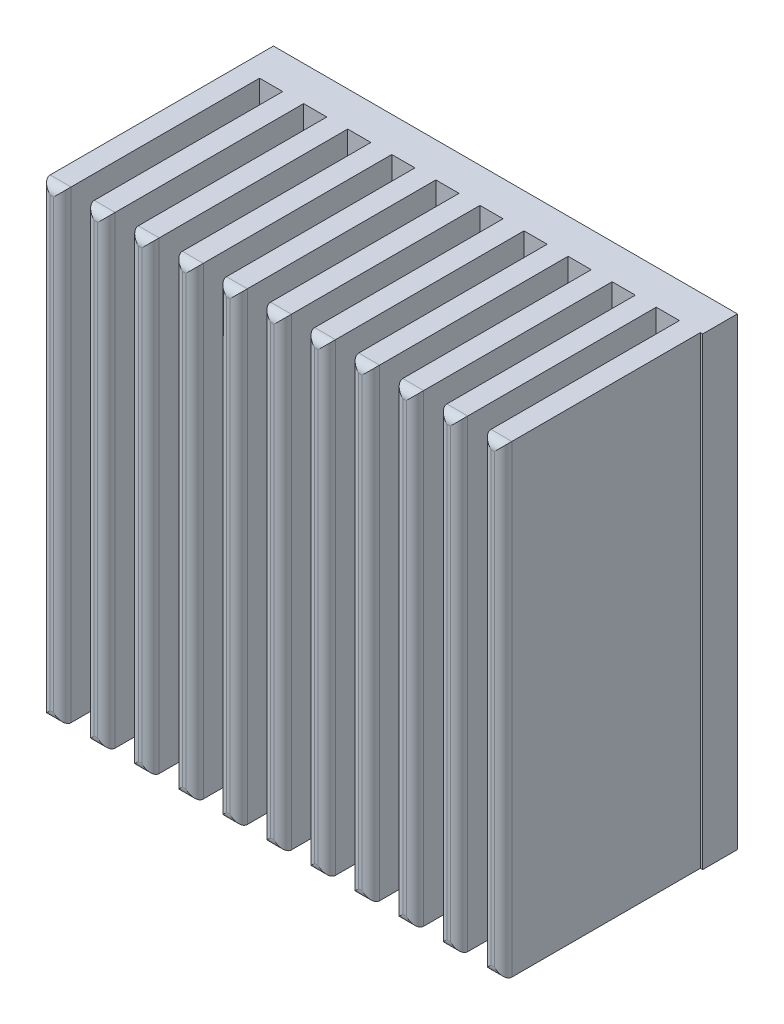
SolidWorks part; units mm, degrees
material "1060 Alloy"
ref_plane "Front Plane" through (0, 0, 0) normal (0, 0, 1) x (1, 0, 0)
ref_plane "Top Plane" through (0, 0, 0) normal (0, 1, 0) x (1, 0, 0)
ref_plane "Right Plane" through (0, 0, 0) normal (1, 0, 0) x (0, 0, -1)
sketch "Sketch1" plane through (0, 0, 0) normal (0, 0, 1) x (1, 0, 0)
  line L1 (20, -20) -> (-20, -20)
  line L2 (20, -20) -> (20, 20)
  line L3 (20, 20) -> (-20, 20)
  line L4 (-20, -20) -> (-20, 20)
  line L5 (20, -20) -> (-20, 20) construction
  line L6 (20, 20) -> (-20, -20) construction
  point P0 (0, 0)
  dimension "D1" = 40
extrude "Boss-Extrude1" add sketch "Sketch1" along normal blind 3
sketch "Sketch2" plane through (0, 0, 3) normal (0, 0, 1) x (1, 0, 0)
  line L0 (-20, -20) -> (20, -20) construction
  line L1 (-20, 20) -> (-18.2, 20)
  line L2 (-20, 20) -> (-20, -20)
  line L3 (-20, -20) -> (-18.2, -20)
  line L4 (-18.2, 20) -> (-18.2, -20)
  dimension "D1" = 1.8
extrude "Boss-Extrude2" add sketch "Sketch2" along normal blind 17
pattern_linear "LPattern1" count 11 spacing 3.8 along (1, 0, 0) of "Boss-Extrude2"
fillet "Fillet1" radius 0.75 44 edges at (-3.9, -20, 20) (-3.9, 20, 20) (-3, 0, 20) (-4.8, 0, 20) (-7.7, -20, 20) (-7.7, 20, 20) (-6.8, 0, 20) (-8.6, 0, 20) (-11.5, -20, 20) (-11.5, 20, 20) (-10.6, 0, 20) (-12.4, 0, 20) (-15.3, -20, 20) (-15.3, 20, 20) (-14.4, 0, 20) (-16.2, 0, 20) (-19.1, 20, 20) (-18.2, 0, 20) (-19.1, -20, 20) (-20, 0, 20) (18.9, -20, 20) (18.9, 20, 20) (19.8, 0, 20) (18, 0, 20) (15.1, -20, 20) (15.1, 20, 20) (16, 0, 20) (14.2, 0, 20) (11.3, -20, 20) (11.3, 20, 20) (12.2, 0, 20) (10.4, 0, 20) (7.5, -20, 20) (7.5, 20, 20) (8.4, 0, 20) (6.6, 0, 20) (3.7, -20, 20) (3.7, 20, 20) (4.6, 0, 20) (2.8, 0, 20) (-0.1, -20, 20) (-0.1, 20, 20) (0.8, 0, 20) (-1, 0, 20)
